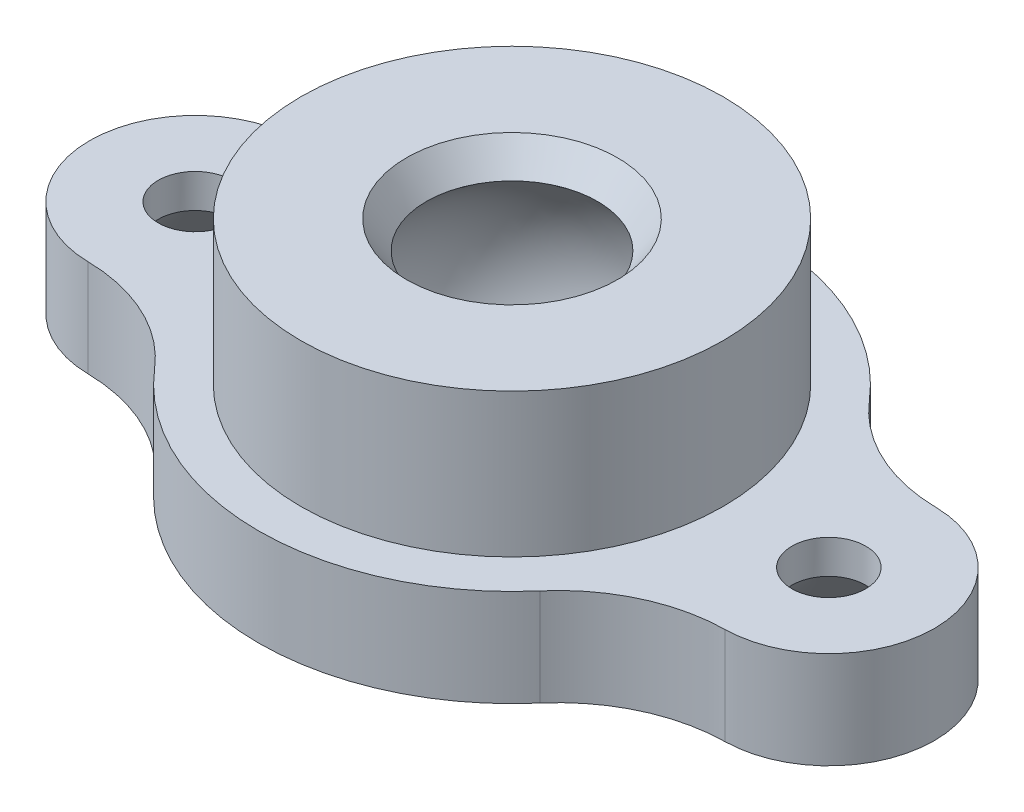
SolidWorks part; units mm, degrees
ref_plane "Plan de face" through (0, 0, 0) normal (0, 0, 1) x (1, 0, 0)
ref_plane "Plan de dessus" through (0, 0, 0) normal (0, 1, 0) x (1, 0, 0)
ref_plane "Plan de droite" through (0, 0, 0) normal (1, 0, 0) x (0, 0, -1)
sketch "Esquisse1" plane through (0, 0, 0) normal (0, 0, 1) x (1, 0, 0)
  line L0 (0, 18.9741) -> (0, -18.6852) construction
  line L1 (-5.9, -3.5777) -> (-7.421, -4.5)
  line L2 (-7.421, -4.5) -> (-20, -4.5)
  line L3 (-10, 0.1) -> (-10, 6.9)
  line L4 (-6.4, 0) -> (-6.4, -8.6639) construction
  line L5 (-10, 6.9) -> (-5, 6.9)
  line L6 (-20, -4.5) -> (-20, 0.1)
  line L7 (-20, 0.1) -> (-10, 0.1)
  line L8 (0, -6.9) -> (-20.1755, -6.9) construction
  line L9 (-5, 6.9) -> (-4.0487, 5.5873)
  circle A0 centre (0, 0) radius 6.4 construction
  arc A1 (-4.0487, 5.5873) -> (-5.9, -3.5777) centre (0, 0) ccw
  dimension "D1" = 12.8
  dimension "D2" = 0.5
  dimension "D3" = 0.5
  dimension "D4" = 4.5
  dimension "D5" = 10
  dimension "D6" = 7
  dimension "D7" = 20
  dimension "D8" = 40
revolve "Révolution1" add sketch "Esquisse1" angle 360 about L0
sketch "Esquisse2" plane through (0, 0.1, 0) normal (0, 1, 0) x (1, 0, 0)
  line L0 (-15, 0) -> (15, 0) construction
  circle A0 centre (-15, 0) radius 1.75
  circle A1 centre (15, 0) radius 1.75
  dimension "D1" = 3.5
  dimension "D2" = 30
extrude "Enlèv. mat.-Extru.1" cut sketch "Esquisse2" against normal through all
chamfer "Chanfrein1" distance 3 angle 45 2 edges at (15, -4.5, 1.75) (-15, -4.5, 1.75)
sketch "Esquisse4" plane through (0, 0.1, 0) normal (0, 1, 0) x (1, 0, 0)
  arc A0 (-9.12, -7.7991) -> (9.12, -7.7991) centre (0, 0) ccw
  arc A1 (-15.0769, 4.9994) -> (-15.0769, -4.9994) centre (-15, 0) ccw
  arc A2 (15.0769, -4.9994) -> (15.0769, 4.9994) centre (15, 0) ccw
  circle A4 centre (0, 0) radius 20 construction
  circle A5 centre (0, 0) radius 10 construction
  arc A6 (9.12, 7.7991) -> (-9.12, 7.7991) centre (0, 0) ccw
  arc A7 (15.0769, -4.9994) -> (9.12, -7.7991) centre (15.2, -12.9985) ccw
  arc A8 (15.0769, 4.9994) -> (9.12, 7.7991) centre (15.2, 12.9985) cw
  arc A9 (-15.0769, -4.9994) -> (-9.12, -7.7991) centre (-15.2, -12.9985) cw
  arc A10 (-15.0769, 4.9994) -> (-9.12, 7.7991) centre (-15.2, 12.9985) ccw
  point P18 (11.4667, 3.5377)
  dimension "D1" = 2
  dimension "D2" = 8
extrude "Enlèv. mat.-Extru.2" cut sketch "Esquisse4" against normal through all flip side to cut
